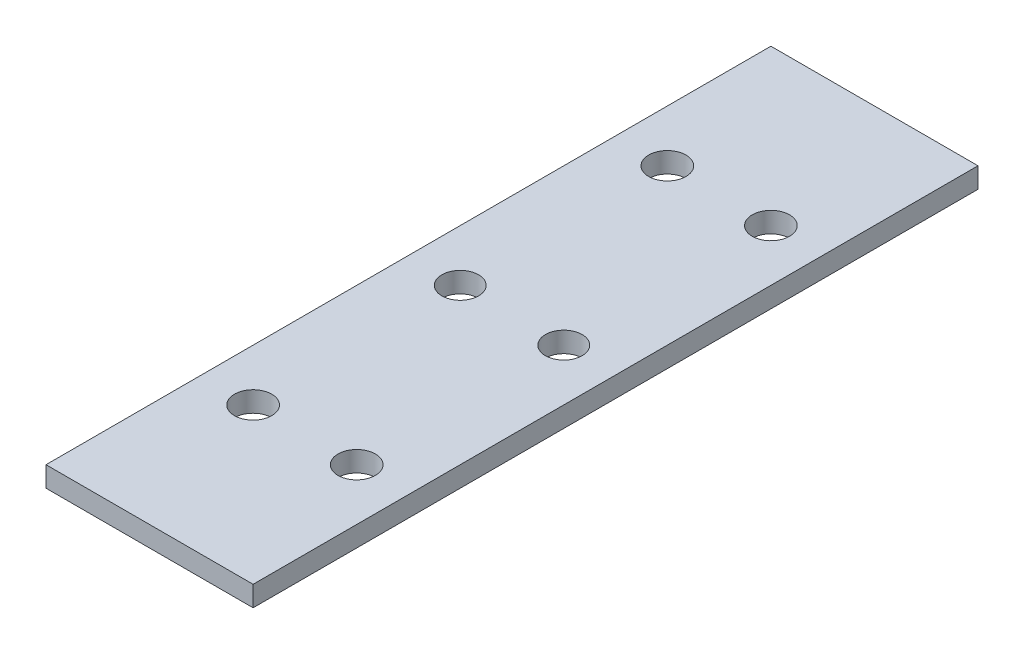
SolidWorks part; units mm, degrees
material "1060 Alloy"
ref_plane "Front Plane" through (0, 0, 0) normal (0, 0, 1) x (1, 0, 0)
ref_plane "Top Plane" through (0, 0, 0) normal (0, 1, 0) x (1, 0, 0)
ref_plane "Right Plane" through (0, 0, 0) normal (1, 0, 0) x (0, 0, -1)
sketch "Sketch1" plane through (0, 0, 0) normal (0, 1, 0) x (1, 0, 0)
  line L0 (0, 88.9) -> (25.4, 0) construction
  line L1 (0, 0) -> (25.4, 0)
  line L2 (0, 0) -> (0, 88.9)
  line L3 (0, 88.9) -> (25.4, 88.9)
  line L4 (25.4, 0) -> (25.4, 88.9)
  line L5 (0, 0) -> (25.4, 88.9) construction
  line L6 (25.4, 44.45) -> (0, 44.45) construction
  line L7 (25.4, 69.85) -> (0, 69.85) construction
  line L8 (25.4, 19.05) -> (0, 19.05) construction
  line L9 (12.7, 88.9) -> (12.7, 0) construction
  line L10 (12.7, 0) -> (0, 88.9) construction
  line L11 (12.7, 88.9) -> (0, 0) construction
  line L12 (6.35, 0) -> (6.35, 88.9) construction
  line L13 (6.35, 88.9) -> (12.7, 88.9) construction
  line L14 (12.7, 88.9) -> (25.4, 0) construction
  line L15 (12.7, 0) -> (25.4, 88.9) construction
  line L16 (19.05, 44.45) -> (19.05, 88.9) construction
  line L17 (19.05, 88.9) -> (19.05, 0) construction
  circle A0 centre (6.35, 69.85) radius 2.286
  circle A1 centre (19.05, 69.85) radius 2.286
  circle A2 centre (19.05, 19.05) radius 2.286
  circle A3 centre (6.35, 19.05) radius 2.286
  circle A4 centre (6.35, 44.45) radius 2.25
  circle A5 centre (19.05, 44.45) radius 2.25
  dimension "D5" = 4.572
  dimension "D6" = 2
  dimension "D7" = 2
  dimension "D8" = 4.5
  dimension "D9" = 4.5
  dimension "D1" = 25.4
  dimension "D2" = 88.9
  dimension "D3" = 25.4
  dimension "D4" = 25.4
  dimension "D10" = 6.35
  dimension "D11" = 0
extrude "Boss-Extrude1" add sketch "Sketch1" along normal blind 2.5
equation "\"D4@Sketch1\"=\"D3@Sketch1\""
